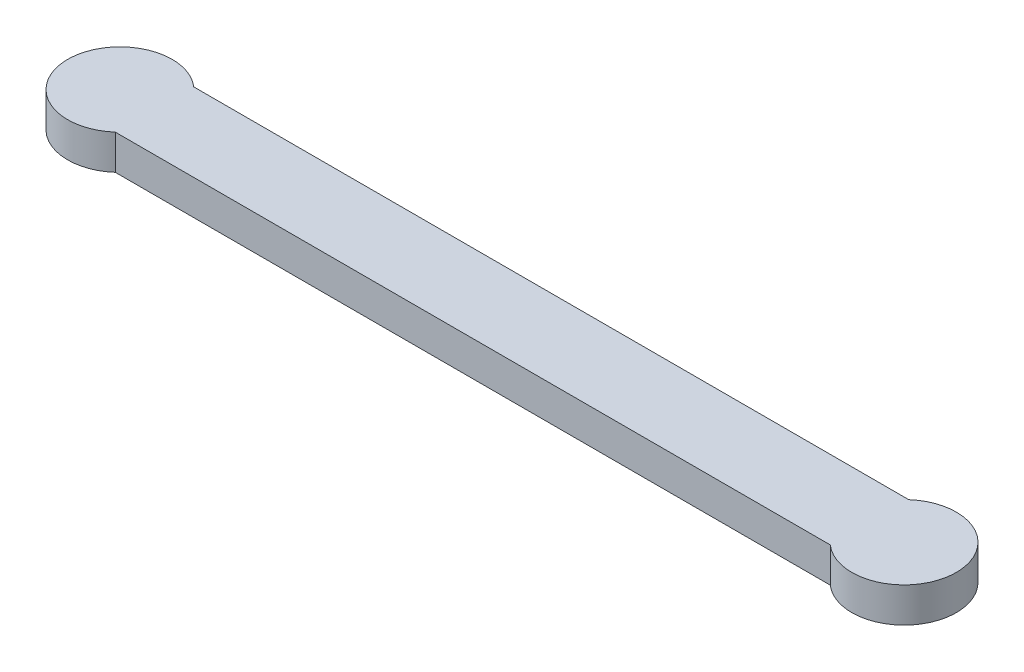
SolidWorks part; units mm, degrees
ref_plane "前视基准面" through (0, 0, 0) normal (0, 0, 1) x (1, 0, 0)
ref_plane "上视基准面" through (0, 0, 0) normal (0, 1, 0) x (1, 0, 0)
ref_plane "右视基准面" through (0, 0, 0) normal (1, 0, 0) x (0, 0, -1)
sketch "草图1" plane through (0, 0, 0) normal (0, 1, 0) x (1, 0, 0)
  line L0 (0, 0) -> (90, 0) construction
  line L1 (0, 4.5) -> (90, 4.5)
  line L2 (0, -4.5) -> (90, -4.5)
  arc A0 (0, 4.5) -> (0, -4.5) centre (0, 0) ccw
  arc A1 (90, -4.5) -> (90, 4.5) centre (90, 0) ccw
  circle A2 centre (0, 0) radius 6
  circle A3 centre (90, 0) radius 6
  point P3 (45, 0)
  dimension "D2" = 4.5
  dimension "D3" = 12
  dimension "D1" = 90
extrude "凸台-拉伸1" add sketch "草图1" along normal blind 4
